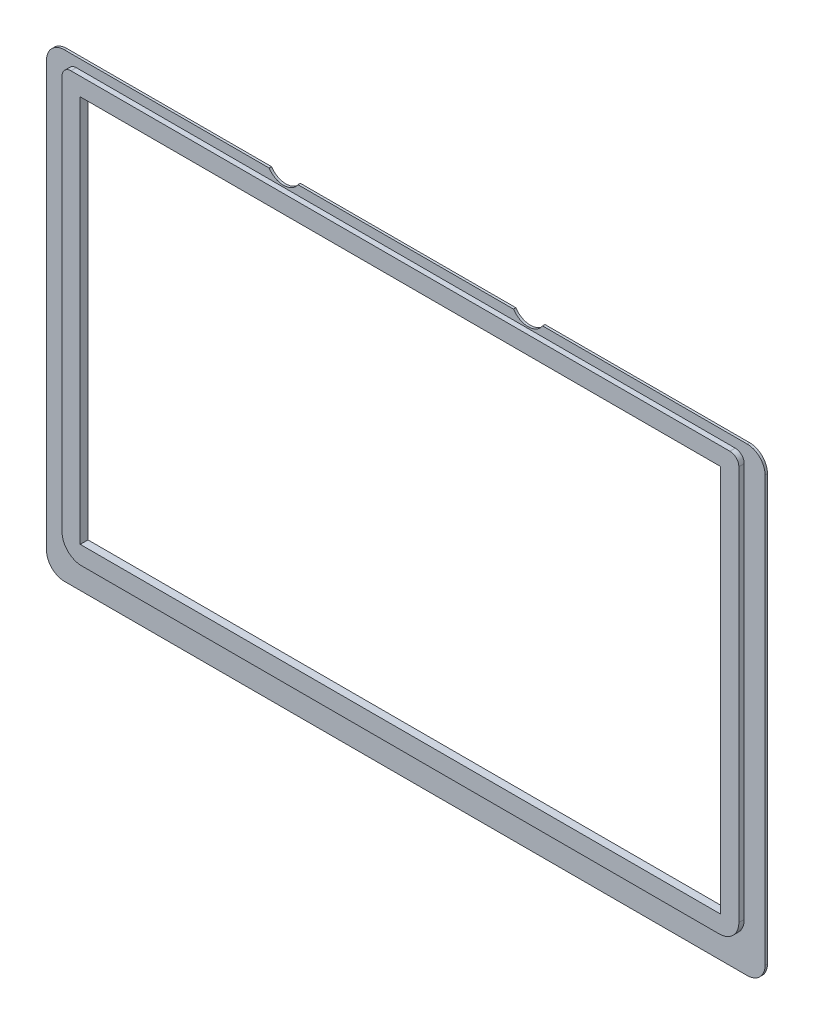
SolidWorks part; units mm, degrees
ref_plane "Ebene vorne" through (0, 0, 0) normal (0, 0, 1) x (1, 0, 0)
ref_plane "Ebene oben" through (0, 0, 0) normal (0, 1, 0) x (1, 0, 0)
ref_plane "Ebene rechts" through (0, 0, 0) normal (1, 0, 0) x (0, 0, -1)
ref_plane "Ebene1" through (0, 0, 19.9) normal (0, 0, 1) x (1, 0, 0)
sketch "Skizze2" plane through (0, 0, 19.9) normal (0, 0, 1) x (1, 0, 0)
  line L5 (56.75, 10.9) -> (-56.75, 10.9)
  line L6 (56.75, 10.9) -> (56.75, 81.9)
  line L7 (56.75, 81.9) -> (-56.75, 81.9)
  line L8 (-56.75, 10.9) -> (-56.75, 81.9)
  line L9 (56.75, 10.9) -> (-56.75, 81.9) construction
  line L10 (56.75, 81.9) -> (-56.75, 10.9) construction
  point P0 (0, 46.4)
  dimension "D1" = 113.5
  dimension "D2" = 71
  dimension "D3" = 46.4
extrude "Aufsatz-Linear austragen1" add sketch "Skizze2" against normal blind 1.3
sketch "Skizze3" plane through (0, 0, 19.9) normal (0, 0, 1) x (1, 0, 0)
  line L1 (60.25, 83.5) -> (-60.25, 83.5)
  line L2 (60.25, 83.5) -> (60.25, 6.3)
  line L3 (60.25, 6.3) -> (-60.25, 6.3)
  line L4 (-60.25, 83.5) -> (-60.25, 6.3)
  point P4 (0, 6.3)
  dimension "D1" = 120.5
  dimension "D2" = 6.3
  dimension "D3" = 83.5
extrude "Aufsatz-Linear austragen2" add sketch "Skizze3" against normal up to surface (0.4 mm away) from offset 0.9 up to face at (0, 46.4, 18.6) offset against normal yes
sketch "Skizze4" plane through (0, 0, 19.9) normal (0, 0, 1) x (1, 0, 0)
  line L1 (-53.7, 78.9) -> (53.7, 78.9)
  line L2 (-53.7, 78.9) -> (-53.7, 13.9)
  line L3 (-53.7, 13.9) -> (53.7, 13.9)
  line L4 (53.7, 78.9) -> (53.7, 13.9)
  point P4 (0, 13.9)
  point P6 (53.7, 46.4)
  dimension "D1" = 65
  dimension "D2" = 107.4
  dimension "D3" = 46.4
extrude "Schnitt-Linear austragen1" cut sketch "Skizze4" against normal through all
fillet "Verrundung1" radius 1.5 2 edges at (56.75, 81.9, 19.45) (-56.75, 81.9, 19.45)
fillet "Verrundung2" radius 3.3 2 edges at (56.75, 10.9, 19.45) (-56.75, 10.9, 19.45)
fillet "Verrundung3" radius 3 4 edges at (-60.25, 6.3, 18.8) (60.25, 6.3, 18.8) (60.25, 83.5, 18.8) (-60.25, 83.5, 18.8)
sketch "Skizze5" plane through (0, 0, 19.9) normal (0, 0, 1) x (1, 0, 0)
  circle A0 centre (20.5, 85.0709) radius 2.9
  circle A1 centre (-20.5, 85.1) radius 2.9
  dimension "D1" = 5.8
extrude "Schnitt-Linear austragen2" cut sketch "Skizze5" against normal through all
other "Körper speichern1"
